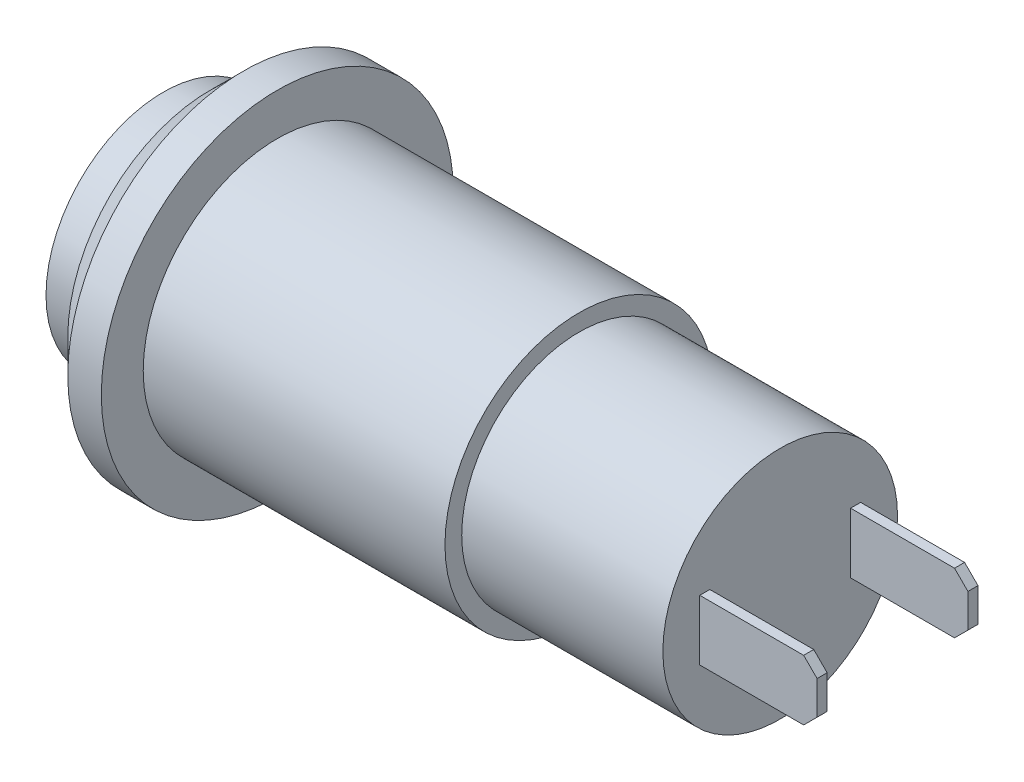
SolidWorks part; units mm, degrees
ref_plane "前视基准面" through (0, 0, 0) normal (0, 0, 1) x (1, 0, 0)
ref_plane "上视基准面" through (0, 0, 0) normal (0, 1, 0) x (1, 0, 0)
ref_plane "右视基准面" through (0, 0, 0) normal (1, 0, 0) x (0, 0, -1)
other "Configuration Table"
sketch "草图1" plane through (0, 0, 0) normal (0, 0, 1) x (1, 0, 0)
  line L0 (0, 0) -> (0, 3.5)
  line L1 (0, 3.5) -> (1.4, 3.5)
  line L2 (1.4, 3.5) -> (1.4, 5.25)
  line L3 (1.4, 5.25) -> (3.4, 5.25)
  line L4 (3.4, 5.25) -> (3.4, 4)
  line L5 (3.4, 4) -> (12.4, 4)
  line L6 (12.4, 4) -> (12.4, 3.5)
  line L7 (12.4, 3.5) -> (18.4, 3.5)
  line L8 (18.4, 3.5) -> (18.4, 0)
  line L9 (18.4, 0) -> (0, 0) construction
  line L10 (0, 0) -> (18.4, 0)
  point P3 (-0.0438, 0)
  point P12 (0, 0)
  dimension "D1" = 18.4
  dimension "D2" = 7
  dimension "D3" = 8
  dimension "D4" = 10.5
  dimension "D5" = 1.4
  dimension "D6" = 2
  dimension "D7" = 9
  dimension "D8" = 7
revolve "旋转1" add sketch "草图1" angle 360 about L9
cosmetic thread "装饰螺纹线1" parameters "D2"=7
chamfer "倒角1" distance 1 angle 45 1 edges at (1.4, 0, -5.25)
sketch "草图2" plane through (18.4, 0, 0) normal (1, 0, 0) x (0, 0, -1)
  line L0 (0, 0) -> (0, 4.3983) construction
  line L1 (-2.25, 0) -> (2.25, 0) construction
  line L3 (-2.4, 0.9) -> (-2.1, 0.9)
  line L4 (-2.4, 0.9) -> (-2.4, -0.9)
  line L5 (-2.4, -0.9) -> (-2.1, -0.9)
  line L6 (-2.1, 0.9) -> (-2.1, -0.9)
  line L7 (-2.4, 0.9) -> (-2.1, -0.9) construction
  line L8 (-2.4, -0.9) -> (-2.1, 0.9) construction
  line L9 (2.1, 0.9) -> (2.4, 0.9)
  line L10 (2.1, 0.9) -> (2.1, -0.9)
  line L11 (2.1, -0.9) -> (2.4, -0.9)
  line L12 (2.4, 0.9) -> (2.4, -0.9)
  line L13 (2.1, 0.9) -> (2.4, -0.9) construction
  line L14 (2.1, -0.9) -> (2.4, 0.9) construction
  point P6 (0, 0)
  dimension "D1" = 4.8
  dimension "D2" = 0.3
  dimension "D3" = 1.8
extrude "凸台-拉伸1" add sketch "草图2" along normal blind 3.5
chamfer "倒角2" distance 0.4 angle 45 4 edges at (21.9, -0.9, -2.25) (21.9, 0.9, -2.25) (21.9, -0.9, 2.25) (21.9, 0.9, 2.25)
